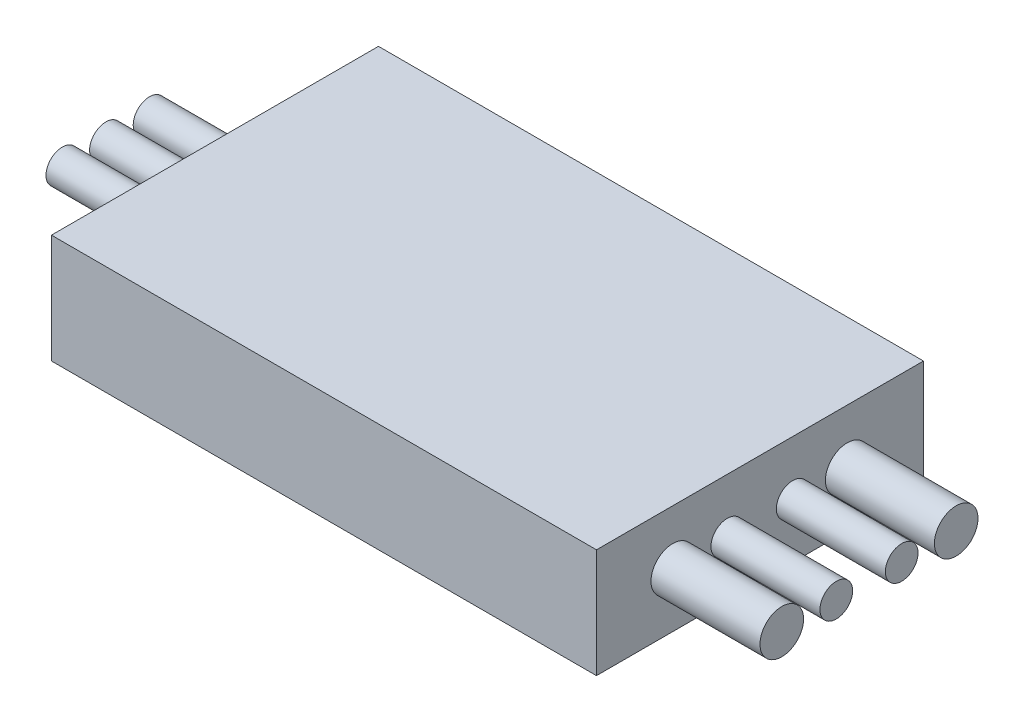
SolidWorks part; units mm, degrees
ref_plane "Front Plane" through (0, 0, 0) normal (0, 0, 1) x (1, 0, 0)
ref_plane "Top Plane" through (0, 0, 0) normal (0, 1, 0) x (1, 0, 0)
ref_plane "Right Plane" through (0, 0, 0) normal (1, 0, 0) x (0, 0, -1)
sketch "Sketch1" plane through (0, 0, 0) normal (0, 1, 0) x (1, 0, 0)
  line L1 (0, 0) -> (25, 0)
  line L2 (0, 0) -> (0, 15)
  line L3 (0, 15) -> (25, 15)
  line L4 (25, 0) -> (25, 15)
  dimension "D1" = 25
  dimension "D2" = 15
extrude "Boss-Extrude1" add sketch "Sketch1" along normal blind 5
sketch "Sketch2" plane through (25, 0, 0) normal (1, 0, 0) x (0, 0, -1)
  line L0 (0, 2.5) -> (15, 2.5) construction
  line L1 (0, 5) -> (0, 0) construction
  line L2 (15, 5) -> (15, 0) construction
  line L3 (7.5, 2.5) -> (7.5, 5) construction
  line L4 (0, 5) -> (15, 5) construction
  circle A0 centre (11.5, 2.5) radius 1
  circle A1 centre (6, 2.5) radius 0.75
  circle A2 centre (9, 2.5) radius 0.75
  circle A3 centre (3.5, 2.5) radius 1
  dimension "D1" = 2
  dimension "D2" = 2
  dimension "D3" = 1.5
  dimension "D4" = 1.5
  dimension "D5" = 1.5
  dimension "D6" = 4
extrude "Boss-Extrude2" add sketch "Sketch2" along normal blind 5
sketch "Sketch3" plane through (0, 0, 0) normal (-1, 0, 0) x (0, 0, 1)
  line L0 (-15, 2.5) -> (0, 2.5) construction
  line L1 (-15, 5) -> (-15, 0) construction
  line L2 (0, 5) -> (0, 0) construction
  line L3 (-7.5, 2.5) -> (-7.5, 5) construction
  line L4 (-15, 5) -> (0, 5) construction
  circle A0 centre (-9.5, 2.5) radius 0.75
  circle A1 centre (-7.5, 2.5) radius 0.75
  circle A2 centre (-5.5, 2.5) radius 0.75
  dimension "D3" = 1.5
  dimension "D1" = 1.5
  dimension "D2" = 1.5
  dimension "D4" = 2
extrude "Boss-Extrude3" add sketch "Sketch3" along normal blind 5
equation "\"D2@Sketch2\"=\"D1@Sketch2\""
equation "\"D4@Sketch2\"=\"D3@Sketch2\""
equation "\"D2@Sketch3\"=\"D1@Sketch3\""
equation "\"D3@Sketch3\"=\"D1@Sketch3\""
